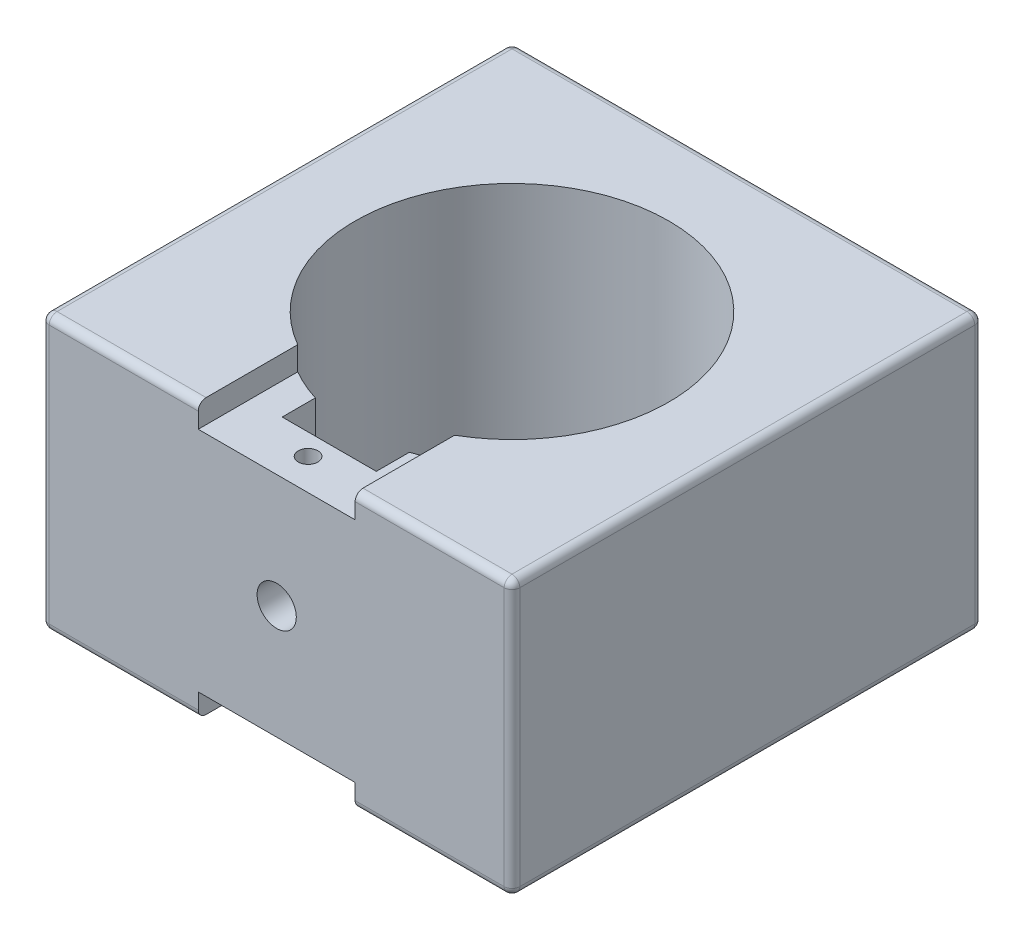
SolidWorks part; units mm, degrees
ref_plane "Plan de face" through (0, 0, 0) normal (0, 0, 1) x (1, 0, 0)
ref_plane "Plan de dessus" through (0, 0, 0) normal (0, 1, 0) x (1, 0, 0)
ref_plane "Plan de droite" through (0, 0, 0) normal (1, 0, 0) x (0, 0, -1)
sketch "Esquisse1" plane through (0, 0, 0) normal (0, 1, 0) x (1, 0, 0)
  line L7 (30, 30) -> (-30, 30)
  line L8 (30, 30) -> (30, -30)
  line L9 (30, -30) -> (-30, -30)
  line L10 (-30, 30) -> (-30, -30)
  line L11 (30, 30) -> (-30, -30) construction
  line L12 (30, -30) -> (-30, 30) construction
  circle A0 centre (0, 0) radius 20
  point P0 (0, 0)
  point P6 (0, 0)
  dimension "D2" = 40
  dimension "D1" = 60
extrude "Boss.-Extru.1" add sketch "Esquisse1" along normal blind 35
fillet "Congé1" radius 1 12 edges at (-30, 35, 0) (-30, 0, 0) (-30, 17.5, 30) (0, 35, 30) (0, 0, 30) (0, 35, -30) (-30, 17.5, -30) (0, 0, -30) (30, 17.5, 30) (30, 35, 0) (30, 17.5, -30) (30, 0, 0)
hole_wizard "Trou taraudé M61" positions "Esquisse4" profile "Esquisse5" tap size "M6" standard "DIN"
sketch "Esquisse4" plane through (0, 0, 30) normal (0, 0, 1) x (1, 0, 0)
  line L0 (0, 34) -> (0, 1) construction
  line L1 (29, 34) -> (-29, 34) construction
  line L2 (-29, 1) -> (29, 1) construction
  point P0 (0, 17.5)
sketch "Esquisse5" plane through (0, 17.5, 30) normal (1, 0, 0) x (0, -1, 0)
  line L0 (0, 0) -> (0, 10)
  line L1 (0, 10) -> (2.5, 10)
  line L2 (2.5, 10) -> (2.5, 0)
  line L5 (2.5, 0) -> (0, 0)
  line L11 (0, -6.35) -> (0, 107.95) construction
  dimension "Diamètre du trou pour taraudage jusqu'au prochain" = 5
  dimension "Profondeur du trou pour taraudage jusqu'au prochain" = 10
cosmetic thread "Filetage de perçage1" parameters "D2"=6
hole_wizard "Trou taraudé M41" positions "Esquisse6" profile "Esquisse7" tap size "M4" standard "DIN"
sketch "Esquisse6" plane through (0, 0, -30) normal (0, 0, -1) x (-1, 0, 0)
  line L0 (0, 1) -> (0, 5.8) construction
  line L1 (-29, 1) -> (29, 1) construction
  line L2 (0, 5.8) -> (0, 29.2) construction
  line L3 (0, 29.2) -> (0, 34) construction
  line L4 (29, 34) -> (-29, 34) construction
  point P0 (0, 29.2)
  point P2 (0, 5.8)
  dimension "D1" = 23.4
sketch "Esquisse7" plane through (0, 29.2, -30) normal (1, 0, 0) x (0, 1, 0)
  line L0 (0, 0) -> (0, 8.4914)
  line L1 (0, 8.4914) -> (1.65, 7.5)
  line L2 (1.65, 7.5) -> (1.65, 0)
  line L5 (1.65, 0) -> (0, 0)
  line L10 (0, 8.4914) -> (-1.65, 7.5) construction
  line L11 (0, -6.35) -> (0, 107.95) construction
  dimension "Diamètre du trou pour taraudage" = 3.3
  dimension "Profondeur du trou pour taraudage" = 7.5
  dimension "Angle de pointe" = 118
cosmetic thread "Filetage de perçage2" parameters "D1"=4, "D2"=4
cosmetic thread "Filetage de perçage3" parameters "D1"=4, "D2"=4
hole_wizard "Trou taraudé M42" positions "Esquisse8" profile "Esquisse9" tap size "M4" standard "DIN"
sketch "Esquisse8" plane through (-30, 0, 0) normal (-1, 0, 0) x (0, 0, 1)
  line L3 (-29, 17.5) -> (-9.6667, 17.5) construction
  line L4 (-29, 34) -> (-29, 1) construction
  line L5 (-9.6667, 17.5) -> (9.6667, 17.5) construction
  line L6 (9.6667, 17.5) -> (29, 17.5) construction
  line L7 (29, 1) -> (29, 34) construction
  point P0 (-9.6667, 17.5)
sketch "Esquisse9" plane through (-30, 17.5, -9.6667) normal (0, 1, 0) x (0, 0, 1)
  line L0 (0, 0) -> (0, 11.4914)
  line L1 (0, 11.4914) -> (1.65, 10.5)
  line L2 (1.65, 10.5) -> (1.65, 0)
  line L5 (1.65, 0) -> (0, 0)
  line L10 (0, 11.4914) -> (-1.65, 10.5) construction
  line L11 (0, -6.35) -> (0, 107.95) construction
  dimension "Diamètre du trou pour taraudage" = 3.3
  dimension "Profondeur du trou pour taraudage" = 10.5
  dimension "Angle de pointe" = 118
cosmetic thread "Filetage de perçage6" parameters "D1"=7, "D2"=4
sketch "Esquisse10" plane through (0, 0, 0) normal (0, -1, 0) x (1, 0, 0)
  line L0 (6, 23.3) -> (6, 19.0788)
  line L1 (6, 23.3) -> (-6, 23.3)
  line L2 (-6, 23.3) -> (-6, 19.0788)
  line L3 (-6, 20) -> (6, 20) construction
  circle A0 centre (0, 0) radius 20 construction
  arc A1 (6, 19.0788) -> (-6, 19.0788) centre (0, 0) ccw
  dimension "D1" = 12
  dimension "D2" = 3.3
extrude "Enlèv. mat.-Extru.1" cut sketch "Esquisse10" against normal up to next
ref_plane "Plan1" through (0, 17.5, 0) normal (0, -1, 0) x (-1, 0, 0)
sketch "Esquisse11" plane through (0, 0, 0) normal (0, -1, 0) x (1, 0, 0)
  line L0 (-10, 30) -> (-10, 17.3205)
  line L1 (-10, 30) -> (10, 30)
  line L2 (10, 30) -> (10, 17.3205)
  line L3 (-29, 30) -> (29, 30) construction
  arc A0 (-6, 19.0788) -> (6, 19.0788) centre (0, 0) ccw construction
  arc A1 (-10, 17.3205) -> (10, 17.3205) centre (0, 0) cw
  arc A2 (-6, 19.0788) -> (6, 19.0788) centre (0, 0) ccw construction
  dimension "D1" = 20
extrude "Enlèv. mat.-Extru.2" cut sketch "Esquisse11" against normal blind 3
hole_wizard "Trou taraudé M31" positions "Esquisse12" profile "Esquisse13" tap size "M3" standard "DIN"
sketch "Esquisse12" plane through (0, 3, 0) normal (0, -1, 0) x (-1, 0, 0)
  line L0 (0, -23.3) -> (0, -30) construction
  line L1 (-6, -23.3) -> (6, -23.3) construction
  line L2 (-10, -30) -> (10, -30) construction
  point P2 (0, -26)
  dimension "D1" = 4
sketch "Esquisse13" plane through (0, 3, 26) normal (1, 0, 0) x (0, 0, -1)
  line L0 (0, 0) -> (0, 9.2511)
  line L1 (0, 9.2511) -> (1.25, 8.5)
  line L2 (1.25, 8.5) -> (1.25, 0)
  line L5 (1.25, 0) -> (0, 0)
  line L10 (0, 9.2511) -> (-1.25, 8.5) construction
  line L11 (0, -6.35) -> (0, 107.95) construction
  dimension "Diamètre du trou pour taraudage" = 2.5
  dimension "Profondeur du trou pour taraudage" = 8.5
  dimension "Angle de pointe" = 118
cosmetic thread "Filetage de perçage5" parameters "D1"=6, "D2"=3
mirror "Symétrie1" about plane through (0, 17.5, 0) normal (0, -1, 0) of "Trou taraudé M31", "Enlèv. mat.-Extru.2"
equation "\"d1\"= 10"
equation "\"d2\"= 2"
equation "\"d3\"= 30"
